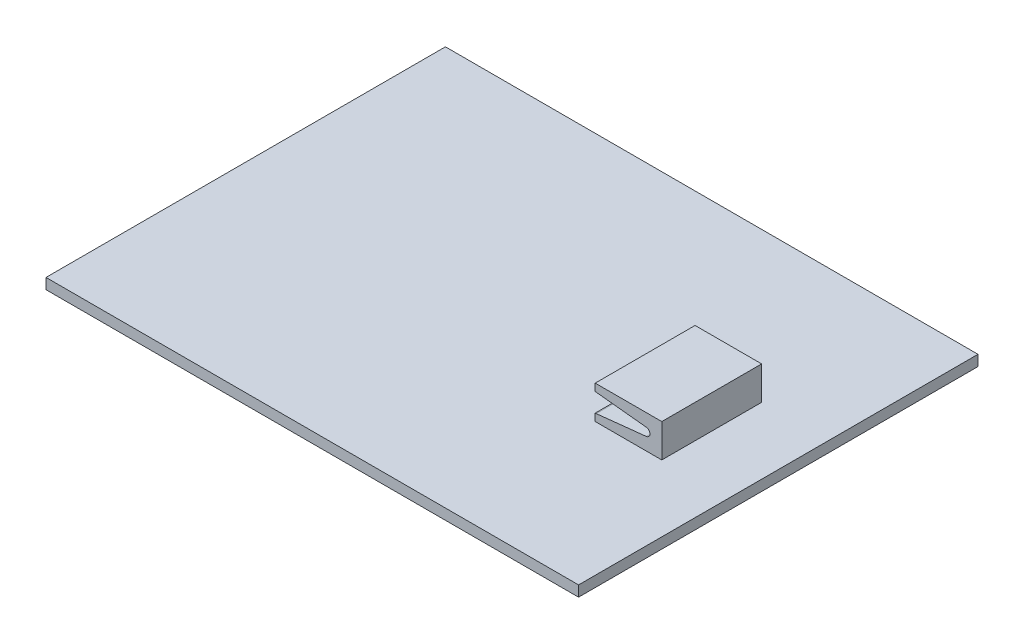
SolidWorks part; units mm, degrees
ref_plane "Front Plane" through (0, 0, 0) normal (0, 0, 1) x (1, 0, 0)
ref_plane "Top Plane" through (0, 0, 0) normal (0, 1, 0) x (1, 0, 0)
ref_plane "Right Plane" through (0, 0, 0) normal (1, 0, 0) x (0, 0, -1)
sketch "Sketch1" plane through (0, 0, 0) normal (0, 1, 0) x (1, 0, 0)
  line L1 (-400, -300) -> (400, -300)
  line L2 (-400, -300) -> (-400, 300)
  line L3 (-400, 300) -> (400, 300)
  line L4 (400, -300) -> (400, 300)
  line L5 (-400, -300) -> (400, 300) construction
  line L6 (-400, 300) -> (400, -300) construction
  point P0 (0, 0)
  dimension "D1" = 600
  dimension "D2" = 800
extrude "Boss-Extrude1" add sketch "Sketch1" along normal blind 16 contours L2 L3 L4 L1
sketch "Sketch2" plane through (0, 16, 0) normal (0, 1, 0) x (1, 0, 0)
  line L0 (-400, 0) -> (250, 0) construction
  line L1 (-400, -300) -> (-400, 300) construction
  line L3 (200, 75) -> (300, 75)
  line L4 (200, 75) -> (200, -75)
  line L5 (200, -75) -> (300, -75)
  line L6 (300, 75) -> (300, -75)
  line L7 (200, 75) -> (300, -75) construction
  line L8 (200, -75) -> (300, 75) construction
  point P9 (300, 0)
  dimension "D1" = 100
  dimension "D2" = 150
extrude "Boss-Extrude2" add sketch "Sketch2" along normal blind 50
sketch "Sketch3" plane through (0, 0, -75) normal (0, 0, -1) x (-1, 0, 0)
  line L0 (-300, 66) -> (-300, 16) construction
  line L1 (-300, 41) -> (-200, 41) construction
  line L2 (-200, 66) -> (-200, 16) construction
  line L3 (-276.863, 46.9669) -> (-201.4692, 54.9227)
  line L4 (-276.863, 35.0331) -> (-201.4692, 27.0773)
  arc A0 (-276.863, 46.9669) -> (-276.863, 35.0331) centre (-276.2333, 41) ccw
  arc A1 (-201.4692, 27.0773) -> (-201.4692, 54.9227) centre (-200, 41) ccw
  point P7 (-300, 41)
extrude "Cut-Extrude1" cut sketch "Sketch3" against normal through all both and the other way through all
